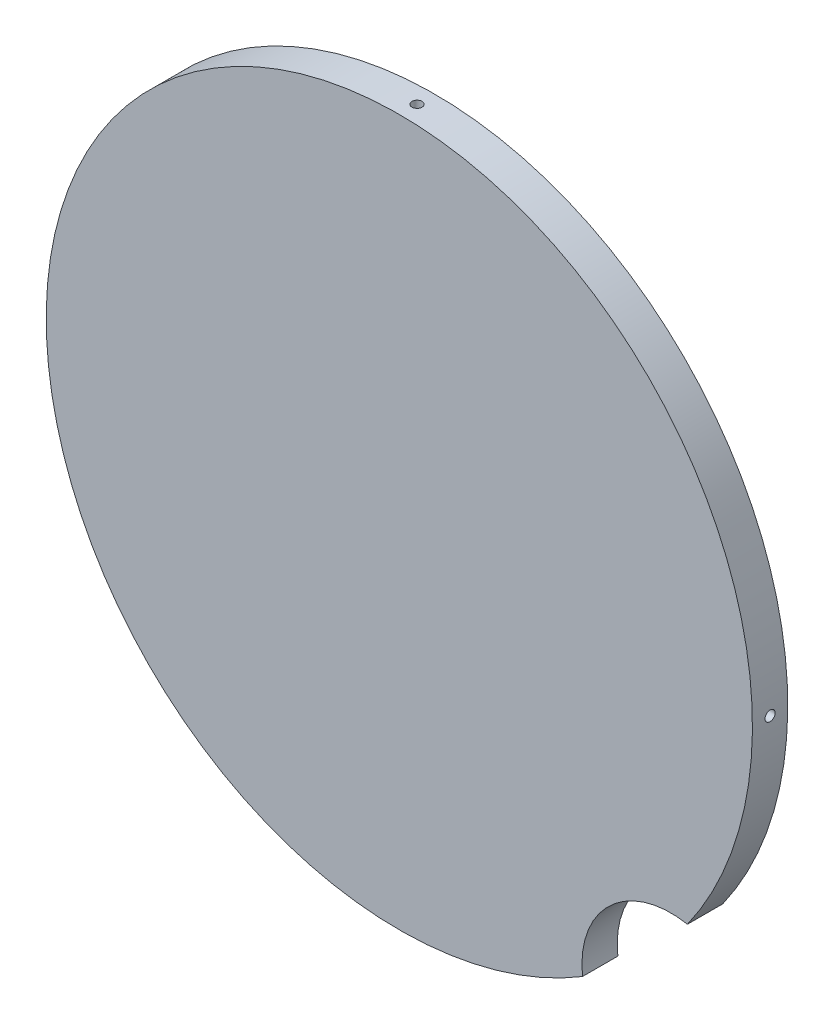
SolidWorks part; units mm, degrees
ref_plane "Front Plane" through (0, 0, 0) normal (0, 0, 1) x (1, 0, 0)
ref_plane "Top Plane" through (0, 0, 0) normal (0, 1, 0) x (1, 0, 0)
ref_plane "Right Plane" through (0, 0, 0) normal (1, 0, 0) x (0, 0, -1)
sketch "Sketch1" plane through (0, 0, 0) normal (0, 0, 1) x (1, 0, 0)
  circle A0 centre (0, 0) radius 70
  dimension "D1" = 140
extrude "Boss-Extrude1" add sketch "Sketch1" along normal blind 7
ref_plane "Plane1" through (0, 70, 0) normal (0, 1, 0) x (1, 0, 0)
sketch "Sketch3" plane through (0, 70, 0) normal (0, 1, 0) x (1, 0, 0)
  line L0 (70, 0) -> (-70, 0) construction
  circle A0 centre (0, -3.5) radius 1
  dimension "D1" = 2
  dimension "D2" = 3.5
extrude "Cut-Extrude1" cut sketch "Sketch3" against normal blind 12 contours A0
pattern_circular "CirPattern1" count 4 every 90 about axis through (0, 0, 0) along (0, 0, 1) of "Cut-Extrude1"
sketch "Sketch4" plane through (0, 0, 0) normal (0, 0, -1) x (-1, 0, 0)
  line L0 (0, 0) -> (67.6148, 18.1173) construction
  line L1 (0, 0) -> (0, 70) construction
  line L2 (3.85, 70) -> (-3.85, 70) construction
  line L3 (0, 0) -> (58.6167, 46.7956) construction
  line L4 (60.8533, 16.3056) -> (66.3622, -4.2538) construction
  line L5 (31.8756, 8.541) -> (48.2963, 12.941)
  line L6 (31.0991, 11.4388) -> (42.6902, 14.5446)
  line L7 (31.0991, 11.4388) -> (31.8756, 8.541)
  line L8 (48.2963, 12.941) -> (45.7081, 22.6002)
  line L9 (42.6902, 14.5446) -> (40.8785, 21.3061)
  line L10 (45.7081, 22.6002) -> (40.8785, 21.3061)
  line L11 (31.0991, 11.4388) -> (47.5198, 15.8387) construction
  line L12 (43.4667, 11.6469) -> (40.8785, 21.3061) construction
  line L13 (48.2963, 12.941) -> (54.1974, -9.0822) construction
  line L14 (51.2468, 1.9294) -> (32.718, -3.0354) construction
  line L15 (56.7856, -18.7414) -> (51.9559, -20.0355)
  line L16 (50.1442, -13.274) -> (51.9559, -20.0355)
  line L17 (54.1974, -9.0822) -> (56.7856, -18.7414)
  line L18 (38.5531, -16.3799) -> (37.7766, -13.4821)
  line L19 (38.5531, -16.3799) -> (50.1442, -13.274)
  line L20 (37.7766, -13.4821) -> (54.1974, -9.0822)
  circle A1 centre (0, 0) radius 70 construction
  dimension "D1" = 75
  dimension "D2" = 63
  dimension "D3" = 50
  dimension "D4" = 17
  dimension "D6" = 10
  dimension "D8" = 22.8
  dimension "D5" = 3
  dimension "D7" = 5
extrude "Boss-Extrude2" add sketch "Sketch4" along normal blind 12 contours L8 L10 L9 L6 L7 L5 | L16 L15 L17 L20 L18 L19
mirror "Mirror1" about plane through (0, 0, 0) normal (1, 0, 0) of "Boss-Extrude2"
sketch "Sketch5" plane through (-48.2963, 12.941, 0) normal (-0.9659, 0.2588, 0) x (0, 0, 1)
  line L0 (0, -25.4) -> (-6.2, -25.4) construction
  line L1 (0, 70) -> (0, -70) construction
  line L2 (-6.2, -25.4) -> (-6.2, -22.8) construction
  line L3 (-12, -22.8) -> (0, -22.8) construction
  circle A0 centre (-6.2, -25.4) radius 1.375
  dimension "D1" = 2.6
  dimension "D2" = 0
  dimension "D3" = 6.2
extrude "Cut-Extrude2" cut sketch "Sketch5" against normal blind 12
sketch "Sketch6" plane through (-48.2963, 12.941, 0) normal (-0.9659, 0.2588, 0) x (0, 0, 1)
  line L0 (0, 0) -> (-6.2, 0)
  line L1 (-12, 0) -> (0, 0) construction
  line L2 (-6.2, 0) -> (-6.2, 2.6)
  circle A0 centre (-6.2, 2.6) radius 1.375
  dimension "D1" = 6.2
  dimension "D2" = 2.6
extrude "Cut-Extrude3" cut sketch "Sketch6" against normal blind 12
mirror "Mirror2" about plane through (0, 0, 0) normal (1, 0, 0) of "Cut-Extrude2", "Cut-Extrude3"
sketch "Sketch7" plane through (0, 0, 0) normal (0, 0, -1) x (-1, 0, 0)
  arc A6 (-57.114, -40.4721) -> (-36.3157, -59.8429) centre (-53.8372, -57.8047) cw
  circle A7 centre (0, 0) radius 70 construction
  arc A8 (-57.114, -40.4721) -> (-36.3157, -59.8429) centre (0, 0) ccw
extrude "Cut-Extrude4" cut sketch "Sketch7" against normal blind 12
